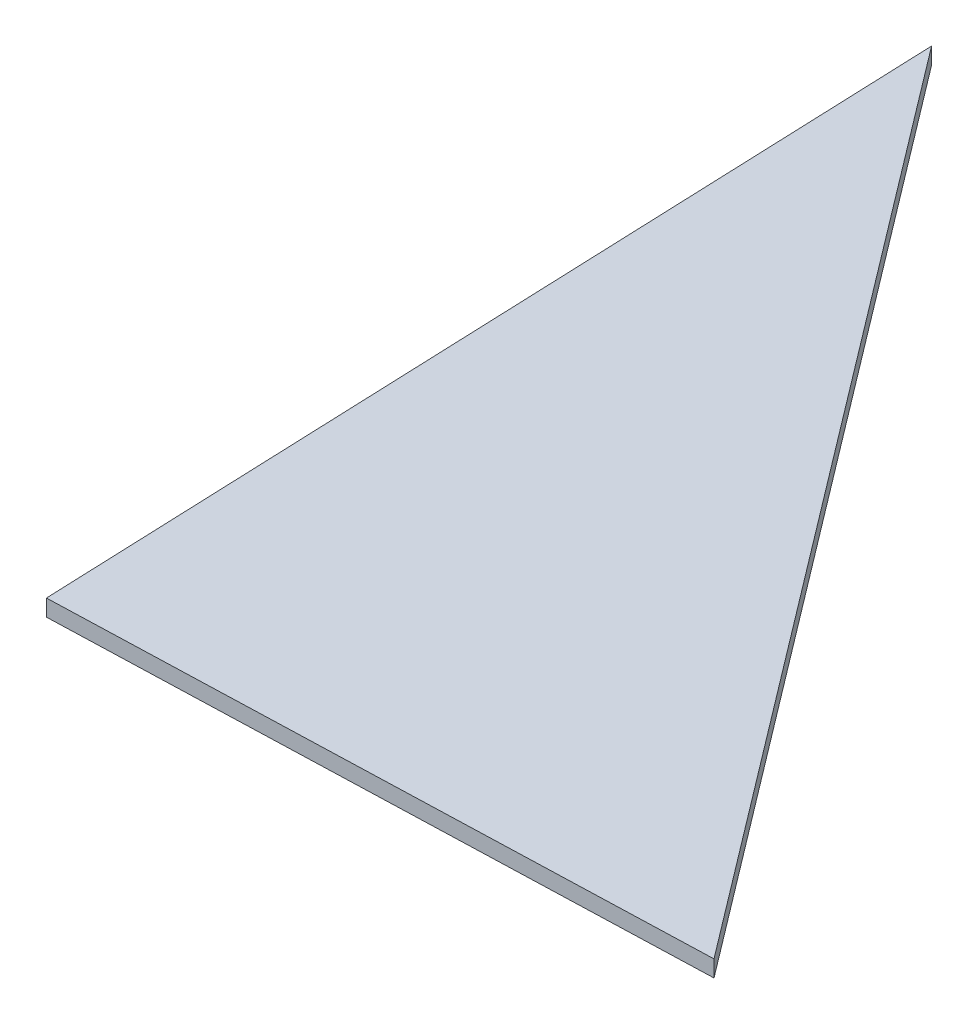
SolidWorks part; units mm, degrees
ref_plane "Front Plane" through (0, 0, 0) normal (0, 0, 1) x (1, 0, 0)
ref_plane "Top Plane" through (0, 0, 0) normal (0, 1, 0) x (1, 0, 0)
ref_plane "Right Plane" through (0, 0, 0) normal (1, 0, 0) x (0, 0, -1)
sketch "Sketch1" plane through (0, 0, 0) normal (0, 1, 0) x (1, 0, 0)
  line L0 (0, 0) -> (4.894, -127)
  line L1 (4.894, -127) -> (94.048, -124.0636)
  line L2 (0, 0) -> (94.048, -124.0636)
  dimension "D1" = 127
  dimension "D2" = 89.154
  dimension "D3" = 155.6817
extrude "Boss-Extrude1" add sketch "Sketch1" along normal blind 2.286
